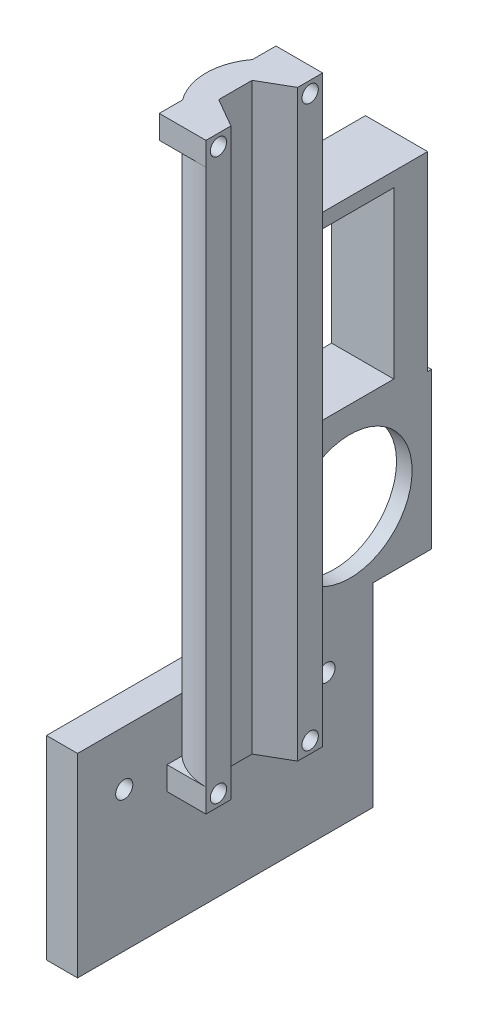
SolidWorks part; units mm, degrees
ref_plane "Front Plane" through (0, 0, 0) normal (0, 0, 1) x (1, 0, 0)
ref_plane "Top Plane" through (0, 0, 0) normal (0, 1, 0) x (1, 0, 0)
ref_plane "Right Plane" through (0, 0, 0) normal (1, 0, 0) x (0, 0, -1)
sketch "Sketch1" plane through (0, 0, 0) normal (0, 1, 0) x (1, 0, 0)
  line L0 (0, 4.2897) -> (0, -4.2897) construction
  line L1 (0, 4.2897) -> (-3.715, 2.1449)
  line L2 (-3.715, 2.1449) -> (-3.715, -2.1449)
  line L3 (-3.715, -2.1449) -> (0, -4.2897)
  line L4 (0, 7.5) -> (0, 4.2897)
  line L5 (0, -4.2897) -> (0, -7.5)
  line L8 (3.715, 2.1449) -> (0, 4.2897) [skipped]
  line L9 (3.715, -2.1449) -> (3.715, 2.1449) [skipped]
  line L10 (0, -4.2897) -> (3.715, -2.1449) [skipped]
  arc A0 (0, 7.5) -> (0, -7.5) centre (0, 0) ccw
  circle A1 centre (0, 0) radius 3.715 construction
  dimension "D1" = 15
  dimension "D2" = 3.715
extrude "Main Body" add sketch "Sketch1" along normal blind 75
ref_plane "Side Extensions Plane" through (-5, 0, 0) normal (1, 0, 0) x (0, 0, -1)
sketch "Sketch6" plane through (-5, 0, 0) normal (1, 0, 0) x (0, 0, -1)
  line L1 (19, 10) -> (-19, 10)
  line L2 (19, 10) -> (19, -15)
  line L3 (19, -15) -> (-19, -15)
  line L4 (-19, 10) -> (-19, -15)
  point P0 (0, 0)
  point P1 (0, 10)
  point P7 (0, 10)
  dimension "D1" = 10
  dimension "D2" = 25
  dimension "D3" = 38
extrude "Base Fit Plate" add sketch "Sketch6" against normal blind 4
sketch "Sketch3" plane through (0, 0, 0) normal (1, 0, 0) x (0, 0, -1)
  line L0 (-4.2897, 75) -> (-4.2897, 0) construction
  line L1 (-7.5, 0) -> (-4.2897, 0)
  line L2 (-7.5, 0) -> (-7.5, 3)
  line L3 (-7.5, 3) -> (-4.2897, 3)
  line L4 (-4.2897, 0) -> (-4.2897, 3)
  line L6 (-7.5, 75) -> (-4.2897, 75)
  line L7 (-7.5, 75) -> (-7.5, 72)
  line L8 (-7.5, 72) -> (-4.2897, 72)
  line L9 (-4.2897, 75) -> (-4.2897, 72)
  dimension "D1" = 3
  dimension "D2" = 3
extrude "Front Screw Holes Support" add sketch "Sketch3" against normal blind 6
sketch "Sketch4" plane through (0, 0, 0) normal (1, 0, 0) x (0, 0, -1)
  line L0 (-7.5, 73.5) -> (-4.2897, 73.5) construction
  line L1 (-7.5, 75) -> (-7.5, 72) construction
  line L2 (-4.2897, 75) -> (-4.2897, 0) construction
  line L3 (-7.5, 1.5) -> (-4.2897, 1.5) construction
  line L4 (-7.5, 3) -> (-7.5, 0) construction
  circle A0 centre (-5.8949, 73.5) radius 1.05
  circle A1 centre (-5.8949, 1.5) radius 1.05
  dimension "D1" = 2.1
  dimension "D2" = 2.1
extrude "Front Screw Holes" cut sketch "Sketch4" against normal up to next
mirror "Back Screw Holes and Support" about plane through (0, 0, 0) normal (0, 0, 1) of "Front Screw Holes", "Front Screw Holes Support"
sketch "Sketch7" plane through (-5, 0, 0) normal (1, 0, 0) x (0, 0, -1)
  line L1 (26.5, 10) -> (-2.5, 10)
  line L2 (26.5, 10) -> (26.5, 30)
  line L3 (26.5, 30) -> (-2.5, 30)
  line L4 (-2.5, 10) -> (-2.5, 30)
  line L5 (26.5, 10) -> (-2.5, 30) construction
  line L6 (26.5, 30) -> (-2.5, 10) construction
  circle A0 centre (16, 20) radius 8
  point P0 (12, 20)
  dimension "D5" = 4
  dimension "D6" = 16
  dimension "D1" = 20
  dimension "D2" = 29
  dimension "D3" = 20
  dimension "D4" = 12
extrude "Button Hole" add sketch "Sketch7" against normal blind 2
sketch "Sketch8" plane through (-5, 0, 0) normal (1, 0, 0) x (0, 0, -1)
  line L1 (26, 29.5) -> (4, 29.5)
  line L2 (26, 29.5) -> (26, 54.5)
  line L3 (26, 54.5) -> (4, 54.5)
  line L4 (4, 29.5) -> (4, 54.5)
  line L5 (26, 29.5) -> (4, 54.5) construction
  line L6 (26, 54.5) -> (4, 29.5) construction
  line L7 (21.65, 31.35) -> (8.35, 31.35)
  line L8 (21.65, 31.35) -> (21.65, 52.65)
  line L9 (21.65, 52.65) -> (8.35, 52.65)
  line L10 (8.35, 31.35) -> (8.35, 52.65)
  line L11 (21.65, 31.35) -> (8.35, 52.65) construction
  line L12 (21.65, 52.65) -> (8.35, 31.35) construction
  point P0 (15, 42)
  point P5 (15, 42)
  dimension "D1" = 25
  dimension "D2" = 22
  dimension "D3" = 42
  dimension "D4" = 15
  dimension "D5" = 21.3
  dimension "D6" = 13.3
extrude "Switch Hole" add sketch "Sketch8" against normal blind 8
sketch "Sketch9" plane through (-9, 0, 0) normal (-1, 0, 0) x (0, 0, 1)
  line L0 (0, 10) -> (0, -15) construction
  line L1 (-19, 10) -> (19, 10) construction
  line L2 (19, -15) -> (-19, -15) construction
  circle A0 centre (-13, 3) radius 1.1
  circle A1 centre (13, 3) radius 1.1
  dimension "D2" = 2.2
  dimension "D1" = 18
  dimension "D3" = 13
extrude "Base Screw Holes" cut sketch "Sketch9" against normal through all
